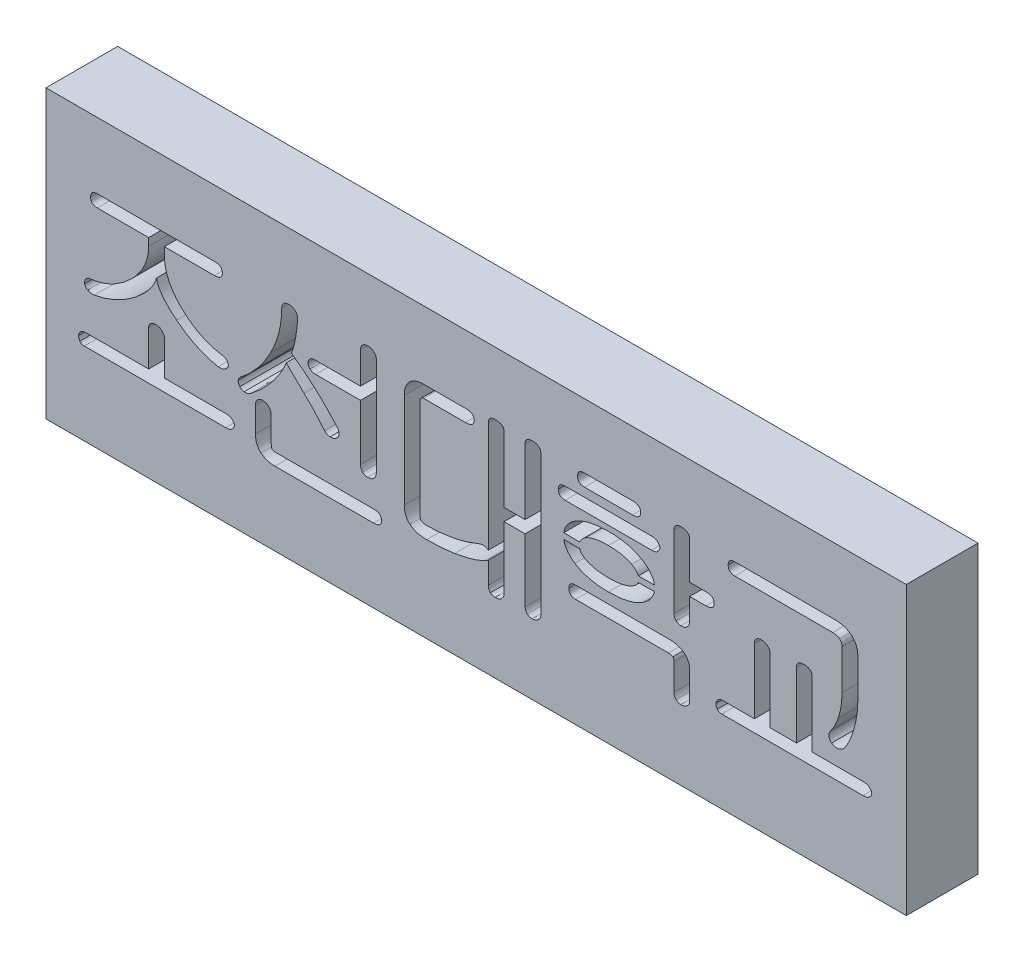
SolidWorks part; units mm, degrees
ref_plane "정면" through (0, 0, 0) normal (0, 0, 1) x (1, 0, 0)
ref_plane "윗면" through (0, 0, 0) normal (0, 1, 0) x (1, 0, 0)
ref_plane "우측면" through (0, 0, 0) normal (1, 0, 0) x (0, 0, -1)
sketch "스케치1" plane through (0, 0, 0) normal (0, 0, 1) x (1, 0, 0)
  line L1 (0, 0) -> (60, 0)
  line L2 (0, 0) -> (0, -20)
  line L3 (0, -20) -> (60, -20)
  line L4 (60, 0) -> (60, -20)
  dimension "D1" = 60
  dimension "D2" = 20
extrude "보스-돌출1" add sketch "스케치1" along normal blind 5
sketch "스케치2" plane through (0, 0, 5) normal (0, 0, 1) x (1, 0, 0)
  line L0 (0, -10) -> (60, -10) construction
  line L1 (0, 0) -> (0, -20) construction
  line L2 (60, -20) -> (60, 0) construction
  text T0 "<b>조선대학교</b>\r\n" font "Century Gothic" height in points 36
other "펜 스케치1"
extrude "컷-돌출1" cut sketch "스케치2" against normal blind 5
sketch "스케치3" plane through (0, 0, 5) normal (0, 0, 1) x (1, 0, 0)
  line L0 (41.3505, -9.0285) -> (42.4495, -9.0151)
  line L1 (37.1985, -9.0285) -> (36.0995, -9.0151)
  line L2 (41.3116, -9.229) -> (42.4519, -9.2151)
  line L3 (37.2307, -8.8289) -> (36.1019, -8.8152)
  line L4 (41.3145, -8.8289) -> (42.4471, -8.8152)
  line L5 (37.2276, -9.2289) -> (36.0971, -9.2151)
  line L6 (37.201, -8.8285) -> (36.1019, -8.8152) construction
  line L7 (37.1961, -9.2285) -> (36.0971, -9.2151) construction
  line L8 (36.1019, -8.8152) -> (36.0995, -9.0151)
  line L9 (36.0971, -9.2151) -> (36.0995, -9.0151)
  line L10 (37.2276, -9.2289) -> (37.1985, -9.0285)
  line L11 (37.2307, -8.8289) -> (37.1985, -9.0285)
  line L12 (41.348, -8.8285) -> (42.4471, -8.8152) construction
  line L13 (41.3529, -9.2285) -> (42.4519, -9.2151) construction
  line L14 (41.3145, -8.8289) -> (41.3505, -9.0285)
  line L15 (41.3116, -9.229) -> (41.3505, -9.0285)
  line L16 (42.4519, -9.2151) -> (42.4495, -9.0151)
  line L17 (42.4471, -8.8152) -> (42.4495, -9.0151)
  spline S0 degree 3 poles (37.1985, -9.0285) (37.1997, -8.9939) (37.2019, -8.9258) (37.2299, -8.8269) (37.2665, -8.7295) (37.3254, -8.639) (37.3975, -8.5512) (37.4852, -8.4677) (37.5899, -8.3894) (37.6663, -8.3417) (37.7061, -8.3168) knots 0 0 0 0 0.112636 0.222117 0.334137 0.451882 0.573068 0.705481 0.846519 1 1 1 1 construction
  spline S1 degree 3 poles (37.6317, -9.6639) (37.5974, -9.6451) (37.5308, -9.6085) (37.4437, -9.5408) (37.3677, -9.4702) (37.3058, -9.3932) (37.2576, -9.3102) (37.2223, -9.2217) (37.2037, -9.1266) (37.2003, -9.0616) (37.1985, -9.0285) knots 0 0 0 0 0.144307 0.280155 0.406502 0.526894 0.643795 0.759889 0.877425 1 1 1 1 construction
  spline S5 degree 3 poles (40.8467, -8.3569) (40.8865, -8.3811) (40.9628, -8.4276) (41.0669, -8.5033) (41.1531, -8.5843) (41.2254, -8.6666) (41.2808, -8.7529) (41.3226, -8.8417) (41.3459, -8.9344) (41.3489, -8.9972) (41.3505, -9.0285) knots 0 0 0 0 0.158723 0.304347 0.437735 0.560662 0.676671 0.786249 0.893465 1 1 1 1 construction
  spline S6 degree 3 poles (41.3505, -9.0285) (41.349, -9.0592) (41.3461, -9.1201) (41.3224, -9.2097) (41.2813, -9.2944) (41.2245, -9.3753) (41.1536, -9.4538) (41.0667, -9.5281) (40.9642, -9.5994) (40.8885, -9.6417) (40.8486, -9.6639) knots 0 0 0 0 0.10785 0.214296 0.323463 0.437745 0.561404 0.694739 0.83947 1 1 1 1 construction
  dimension "D1" = 0.2
  dimension "D2" = 0.2
extrude "보스-돌출2" add sketch "스케치3" against normal blind 5 contours L5 L10 L1 L9 | L11 L3 L8 L1 | L17 L4 L14 L0 | L2 L16 L0 L15
